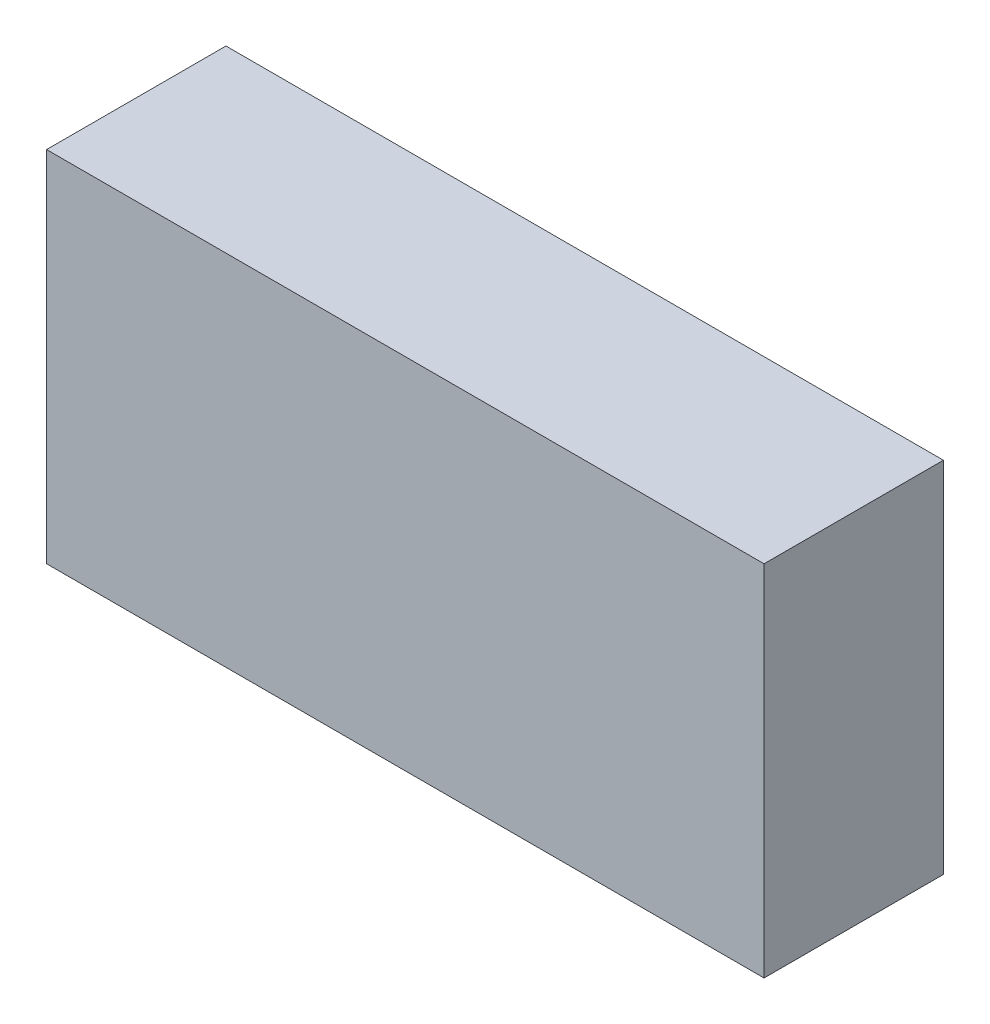
SolidWorks part; units mm, degrees
ref_plane "Front Plane" through (0, 0, 0) normal (0, 0, 1) x (1, 0, 0)
ref_plane "Top Plane" through (0, 0, 0) normal (0, 1, 0) x (1, 0, 0)
ref_plane "Right Plane" through (0, 0, 0) normal (1, 0, 0) x (0, 0, -1)
sketch "Sketch1" plane through (0, 0, 0) normal (0, 0, 1) x (1, 0, 0)
  line L0 (0, 0) -> (40, 0)
  line L1 (40, 0) -> (40, 20)
  line L2 (40, 20) -> (0, 20)
  line L3 (0, 20) -> (0, 0)
extrude "Boss-Extrude1" add sketch "Sketch1" along normal blind 10
